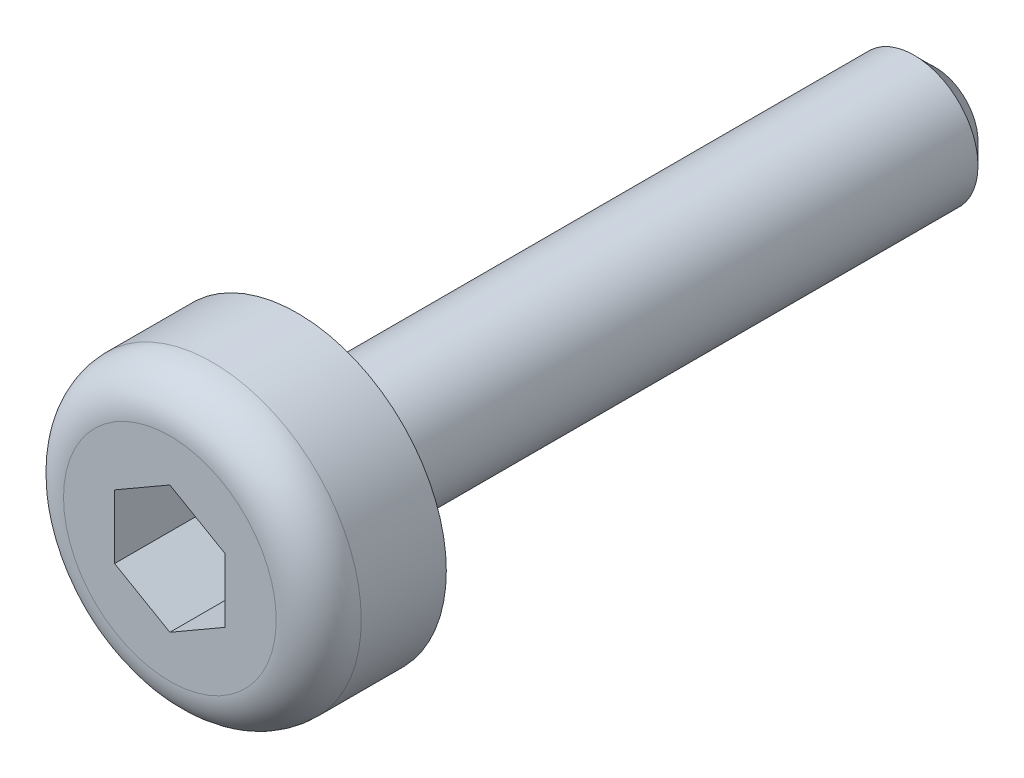
SolidWorks part; units mm, degrees
ref_plane "Front Plane" through (0, 0, 0) normal (0, 0, 1) x (1, 0, 0)
ref_plane "Top Plane" through (0, 0, 0) normal (0, 1, 0) x (1, 0, 0)
ref_plane "Right Plane" through (0, 0, 0) normal (1, 0, 0) x (0, 0, -1)
sketch "Sketch1" plane through (0, 0, 0) normal (1, 0, 0) x (0, 0, -1)
  line L0 (-156.2916, 0) -> (7658.2872, 0) construction
  line L1 (0, 0) -> (0, 3.5)
  line L2 (0, 3.5) -> (3, 3.5)
  line L3 (3, 3.5) -> (3, 1.5)
  line L4 (3, 1.5) -> (18, 1.5)
  line L5 (18, 1.5) -> (18, 0)
  line L6 (18, 0) -> (0, 0)
  dimension "D1" = 3
  dimension "D2" = 15
  dimension "D3" = 3
  dimension "D4" = 7
revolve "Body" add sketch "Sketch1" angle 360 about L0
sketch "Sketch2" plane through (0, 0, 0) normal (0, 0, 1) x (1, 0, 0)
  line L1 (0, 1.5) -> (-1.299, 0.75)
  line L2 (-1.299, 0.75) -> (-1.299, -0.75)
  line L3 (-1.299, -0.75) -> (0, -1.5)
  line L4 (0, -1.5) -> (1.299, -0.75)
  line L5 (1.299, -0.75) -> (1.299, 0.75)
  line L6 (1.299, 0.75) -> (0, 1.5)
  circle A0 centre (0, 0) radius 1.5 construction
  dimension "D1" = 3
extrude "Footprint" cut sketch "Sketch2" against normal blind 2.5
chamfer "Chamfer1" distance 0.5 angle 45 1 edges at (1.5, 0, -18)
fillet "Fillet1" radius 1 1 edges at (3.5, 0, 0)
